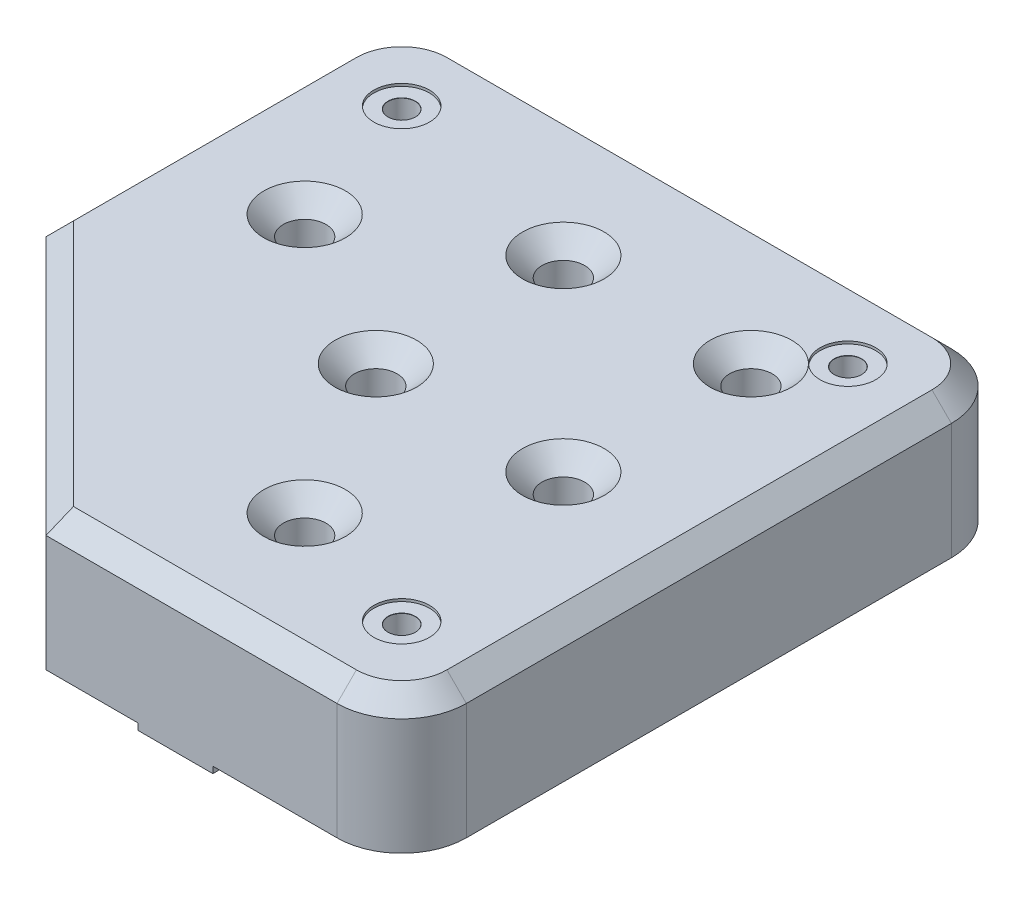
SolidWorks part; units mm, degrees
material "3.1355 (EN-AW 2024)"
ref_plane "Front" through (0, 0, 0) normal (0, 0, 1) x (1, 0, 0)
ref_plane "Top" through (0, 0, 0) normal (0, 1, 0) x (1, 0, 0)
ref_plane "Right" through (0, 0, 0) normal (1, 0, 0) x (0, 0, -1)
sketch "Эскиз1" plane through (0, 0, 0) normal (0, 1, 0) x (1, 0, 0)
  line L1 (-40, 40) -> (40, 40)
  line L2 (-40, 40) -> (-40, -40)
  line L3 (-40, -40) -> (40, -40)
  line L4 (40, 40) -> (40, -40)
  line L5 (-40, 40) -> (40, -40) construction
  line L6 (-40, -40) -> (40, 40) construction
  point P0 (0, 0)
  dimension "D1" = 80
extrude "База" add sketch "Эскиз1" along normal blind 21
sketch "Эскиз11" plane through (0, 21, 0) normal (0, 1, 0) x (1, 0, 0)
  line L1 (40, -40) -> (55, -40)
  line L2 (40, -40) -> (40, 40)
  line L4 (55, -40) -> (55, 55)
  line L6 (-40, 40) -> (40, 40)
  line L7 (-40, 40) -> (-40, 55)
  line L8 (-40, 55) -> (55, 55)
  dimension "D1" = 15
extrude "Вынос" add sketch "Эскиз11" against normal up to surface (21 mm away) up to face at (0, 0, 0)
sketch "Эскиз2" plane through (0, 21, 0) normal (0, 1, 0) x (1, 0, 0)
  line L0 (-40, -40) -> (-40, 0)
  line L1 (-40, 55) -> (-40, -40) construction
  line L2 (-40, 0) -> (0, -40)
  line L3 (-40, -40) -> (55, -40) construction
  line L4 (0, -40) -> (-40, -40)
  dimension "D1" = 40
extrude "Скос" cut sketch "Эскиз2" against normal through all
sketch "Эскиз3" plane through (0, 0, 0) normal (0, -1, 0) x (1, 0, 0)
  line L1 (40, -40) -> (0, -40)
  line L2 (40, -40) -> (40, 0)
  line L3 (40, 0) -> (0, 0)
  line L4 (0, -40) -> (0, 0)
  dimension "D1" = 40
extrude "ВырезПрофиля" cut sketch "Эскиз3" against normal blind 11.5
fillet "Скругление1" radius 2 4 edges at (0, 5.75, 0) (40, 5.75, 0) (40, 5.75, -40) (0, 5.75, -40)
sketch "Эскиз14" plane through (0, 0, 0) normal (0, -1, 0) x (1, 0, 0)
  line L0 (0, -2) -> (0, -38) construction
  line L1 (-40, -14.2) -> (0, -14.2)
  line L2 (-40, -14.2) -> (-40, -25.8)
  line L3 (-40, -25.8) -> (0, -25.8)
  line L4 (0, -14.2) -> (0, -25.8)
  line L5 (-40, -14.2) -> (0, -25.8) construction
  line L6 (-40, -25.8) -> (0, -14.2) construction
  line L7 (38, 0) -> (2, 0) construction
  line L8 (14.2, 40) -> (25.8, 40)
  line L9 (14.2, 40) -> (14.2, 0)
  line L10 (14.2, 0) -> (25.8, 0)
  line L11 (25.8, 40) -> (25.8, 0)
  line L12 (14.2, 40) -> (25.8, 0) construction
  line L13 (14.2, 0) -> (25.8, 40) construction
  line L14 (-40, -55) -> (-40, 0) construction
  line L15 (0, 40) -> (55, 40) construction
  point P0 (-20, -20)
  point P8 (20, 20)
  point P16 (0, -20)
  point P20 (20, 0)
  dimension "D1" = 11.6
extrude "Направляющая" add sketch "Эскиз14" along normal blind 1
hole_wizard "Крепление-M6" positions "Эскиз6" profile "Эскиз8" countersink size "M6" standard "DIN" end condition through all
sketch "Эскиз6" plane through (0, 21, 0) normal (0, 1, 0) x (1, 0, 0)
  line L0 (0, 0) -> (-20, 0) construction
  line L1 (-20, 0) -> (-40, 0) construction
  line L2 (-40, 55) -> (-40, 0) construction
  line L5 (0, 0) -> (20, 0) construction
  line L6 (20, 0) -> (40, 0) construction
  line L10 (0, 0) -> (0, -20) construction
  line L11 (0, -20) -> (0, -40) construction
  line L12 (0, -40) -> (55, -40) construction
  line L15 (0, 0) -> (0, 20) construction
  line L16 (0, 20) -> (0, 40) construction
  line L20 (5.5, 5.5) -> (5.5, 20) construction
  line L21 (5.5, 20) -> (5.5, 34.5) construction
  line L26 (5.5, 5.5) -> (20, 5.5) construction
  line L27 (20, 5.5) -> (34.5, 5.5) construction
  point P0 (-20, 20)
  point P2 (20, -20)
  point P41 (5.5, 34.5)
  point P43 (34.5, 34.5)
  point P45 (34.5, 5.5)
  point P47 (5.5, 5.5)
  dimension "D1" = 29
sketch "Эскиз8" plane through (-20, 21, -20) normal (1, 0, 0) x (0, 0, 1)
  line L0 (0, 0) -> (0, 22)
  line L1 (0, 22) -> (3.3, 22)
  line L2 (3.3, 22) -> (3.3, 3)
  line L3 (3.3, 3) -> (6.3, 0)
  line L5 (6.3, 0) -> (0, 0)
  line L6 (-3.3, 3) -> (-6.3, 0) construction
  line L11 (0, -6.35) -> (0, 107.95) construction
  dimension "Диаметр сквозного отверстия" = 6.6
  dimension "Глубина сквозного отверстия" = 22
  dimension "Диаметр передней зенковки" = 12.6
  dimension "Угол передней зенковки" = 90
hole_wizard "Шкивы-M5" positions "Эскиз12" profile "Эскиз13" tap size "M5" standard "DIN" end condition through all
sketch "Эскиз12" plane through (0, 21, 0) normal (0, 1, 0) x (1, 0, 0)
  line L0 (-27, 42) -> (-40, 42) construction
  line L1 (-40, 55) -> (-40, 0) construction
  line L4 (42, 42) -> (55, 42) construction
  line L5 (55, -40) -> (55, 55) construction
  line L8 (42, -27) -> (42, -40) construction
  line L9 (0, -40) -> (55, -40) construction
  circle A0 centre (20, -20) radius 3.3 construction
  circle A1 centre (-20, 20) radius 3.3 construction
  point P0 (42, 42)
  point P7 (-27, 42)
  point P9 (42, -27)
  dimension "D1" = 22
  dimension "D2" = 22
sketch "Эскиз13" plane through (42, 21, -42) normal (1, 0, 0) x (0, 0, 1)
  line L0 (0, 0) -> (0, 22)
  line L1 (0, 22) -> (2.1, 22)
  line L2 (2.1, 22) -> (2.1, 0.425)
  line L3 (2.1, 0.425) -> (2.525, 0)
  line L5 (2.525, 0) -> (0, 0)
  line L6 (-2.1, 0.425) -> (-2.525, 0) construction
  line L11 (0, -6.35) -> (0, 107.95) construction
  dimension "Диаметр проходного сверла" = 4.2
  dimension "Глубина проходного сверла" = 22
  dimension "Диаметр передней зенковки" = 5.05
  dimension "Угол передней зенковки" = 90
cosmetic thread "Отверстие резьбы1" parameters "D2"=5
cosmetic thread "Отверстие резьбы2" parameters "D2"=5
cosmetic thread "Отверстие резьбы3" parameters "D2"=5
fillet "Скругление2" radius 10 3 edges at (-40, 10.5, -55) (55, 10.5, -55) (55, 10.5, 40)
chamfer "Фаска1" distance 3 angle 45 8 edges at (22.5, 21, 40) (52.0711, 21, 37.0711) (55, 21, -7.5) (52.0711, 21, -52.0711) (7.5, 21, -55) (-37.0711, 21, -52.0711) (-40, 21, -22.5) (-20, 21, 20)
sketch "Эскиз15" plane through (0, 21, 0) normal (0, 1, 0) x (1, 0, 0)
  circle A0 centre (42, 42) radius 4.3
  circle A1 centre (-27, 42) radius 4.3
  circle A2 centre (42, -27) radius 4.3
  dimension "D1" = 8.6
extrude "Вырез-Вытянуть1" cut sketch "Эскиз15" against normal blind 0.4
